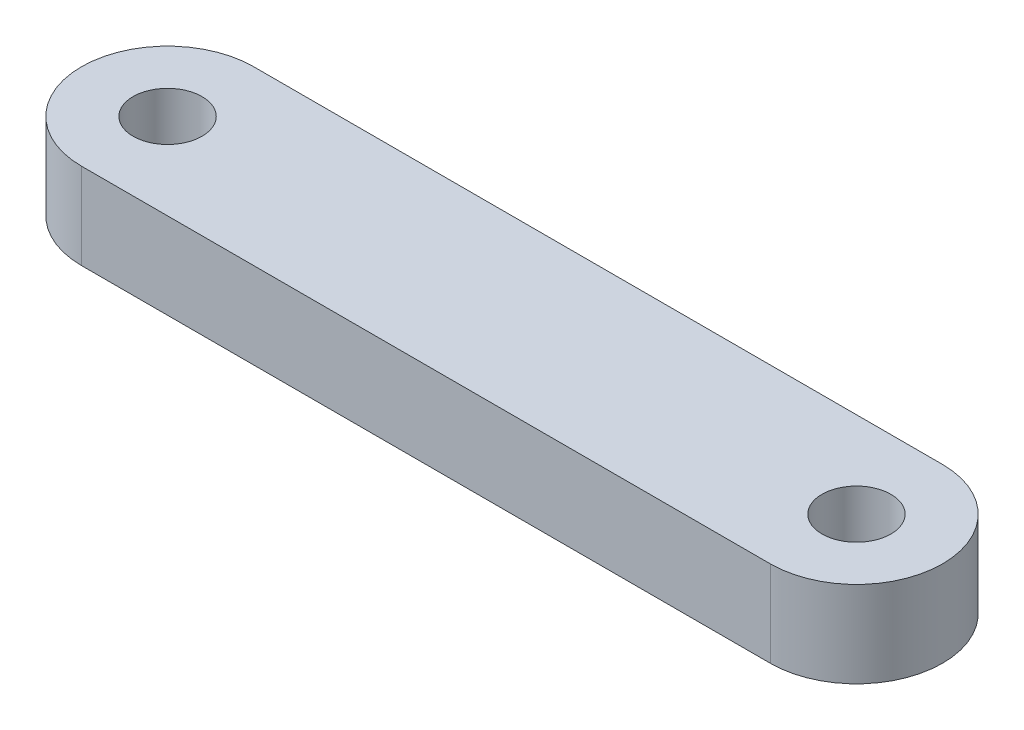
SolidWorks part; units mm, degrees
ref_plane "Front Plane" through (0, 0, 0) normal (0, 0, 1) x (1, 0, 0)
ref_plane "Top Plane" through (0, 0, 0) normal (0, 1, 0) x (1, 0, 0)
ref_plane "Right Plane" through (0, 0, 0) normal (1, 0, 0) x (0, 0, -1)
sketch "Sketch1" plane through (0, 0, 0) normal (0, 1, 0) x (1, 0, 0)
  line L0 (-58.5993, 0) -> (341.4007, 0) construction
  line L1 (-58.5993, 50) -> (341.4007, 50)
  line L2 (-58.5993, -50) -> (341.4007, -50)
  arc A0 (-58.5993, 50) -> (-58.5993, -50) centre (-58.5993, 0) ccw
  arc A1 (341.4007, -50) -> (341.4007, 50) centre (341.4007, 0) ccw
  point P3 (141.4007, 0)
  point P8 (0, 0)
extrude "Boss-Extrude1" add sketch "Sketch1" along normal blind 50
sketch "Sketch2" plane through (0, 50, 0) normal (0, 1, 0) x (1, 0, 0)
  circle A0 centre (-58.5993, 0) radius 20
  circle A1 centre (341.4007, 0) radius 20
extrude "Cut-Extrude1" cut sketch "Sketch2" against normal blind 50
